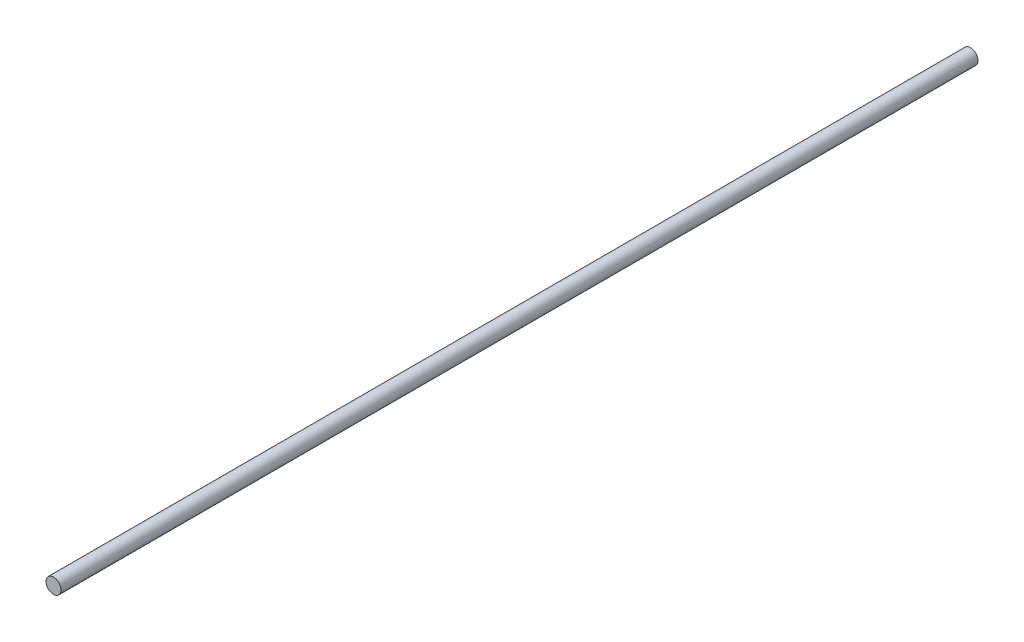
SolidWorks part; units mm, degrees
ref_plane "Front Plane" through (0, 0, 0) normal (0, 0, 1) x (1, 0, 0)
ref_plane "Top Plane" through (0, 0, 0) normal (0, 1, 0) x (1, 0, 0)
ref_plane "Right Plane" through (0, 0, 0) normal (1, 0, 0) x (0, 0, -1)
sketch "Sketch1" plane through (0, 0, 0) normal (0, 0, 1) x (1, 0, 0)
  circle A0 centre (0, 0) radius 6.35
  dimension "D1" = 12.7
extrude "Boss-Extrude1" add sketch "Sketch1" against normal blind 774.7
